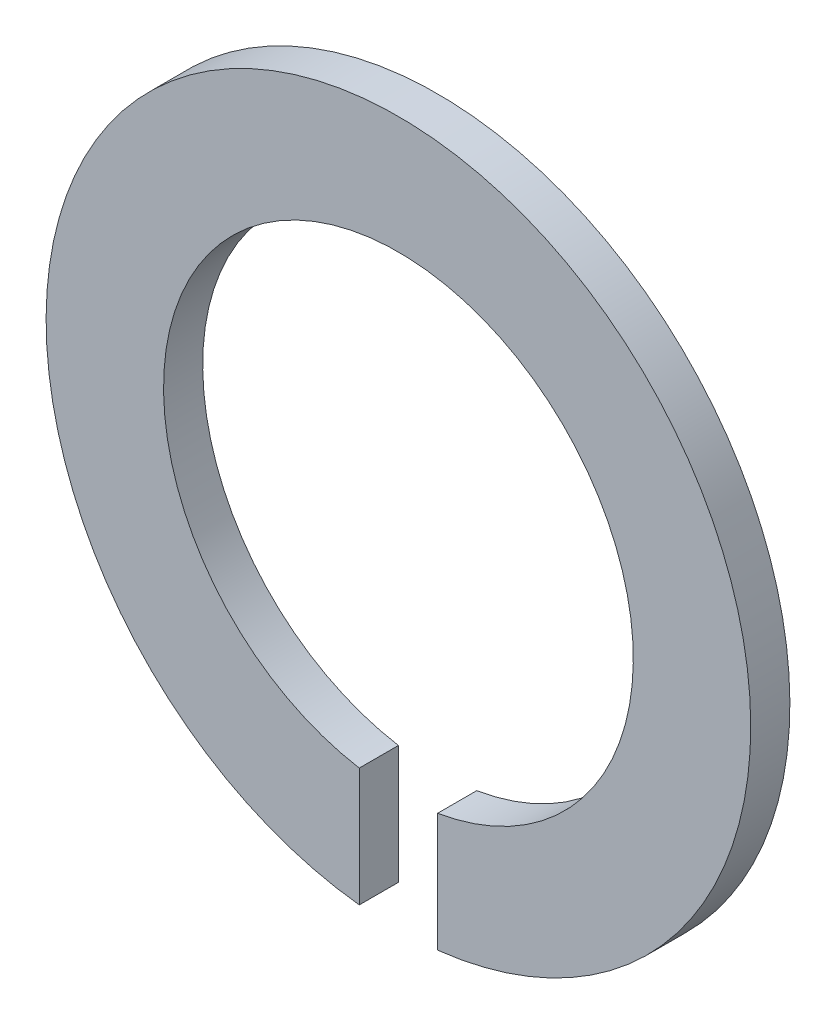
SolidWorks part; units mm, degrees
ref_plane "Plan de face" through (0, 0, 0) normal (0, 0, 1) x (1, 0, 0)
ref_plane "Plan de dessus" through (0, 0, 0) normal (0, 1, 0) x (1, 0, 0)
ref_plane "Plan de droite" through (0, 0, 0) normal (1, 0, 0) x (0, 0, -1)
sketch "Esquisse2" plane through (0, 0, 0) normal (0, 0, 1) x (1, 0, 0)
  line L0 (0, 0) -> (0, -4.3237) construction
  line L1 (0.5, -4.4721) -> (0.5, -2.958)
  line L2 (-0.5, -4.4721) -> (-0.5, -2.958)
  arc A0 (0.5, -2.958) -> (-0.5, -2.958) centre (0, 0) ccw
  arc A1 (0.5, -4.4721) -> (-0.5, -4.4721) centre (0, 0) ccw
  dimension "D1" = 6
  dimension "D2" = 9
  dimension "D3" = 0.5
extrude "Boss.-Extru.1" add sketch "Esquisse2" along normal blind 0.5
